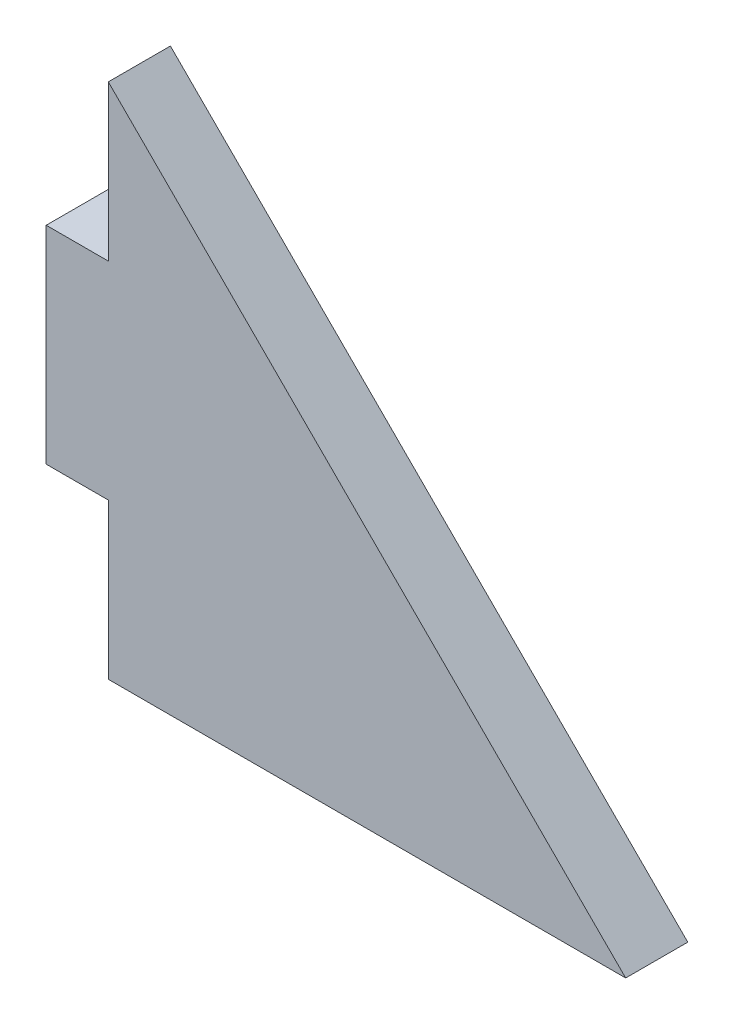
SolidWorks part; units mm, degrees
ref_plane "Front Plane" through (0, 0, 0) normal (0, 0, 1) x (1, 0, 0)
ref_plane "Top Plane" through (0, 0, 0) normal (0, 1, 0) x (1, 0, 0)
ref_plane "Right Plane" through (0, 0, 0) normal (1, 0, 0) x (0, 0, -1)
sketch "Sketch1" plane through (0, 0, 0) normal (0, 0, 1) x (1, 0, 0)
  line L0 (0, 0) -> (0, 7.5)
  line L1 (0, 25) -> (25, 0)
  line L2 (25, 0) -> (0, 0)
  line L3 (0, 17.5) -> (0, 25)
  line L4 (0, 17.5) -> (-3, 17.5)
  line L6 (0, 7.5) -> (-3, 7.5)
  line L7 (-3, 17.5) -> (-3, 7.5)
  dimension "D1" = 10
  dimension "D2" = 3
  dimension "D3" = 25
  dimension "D4" = 25
extrude "Boss-Extrude1" add sketch "Sketch1" along normal blind 3
